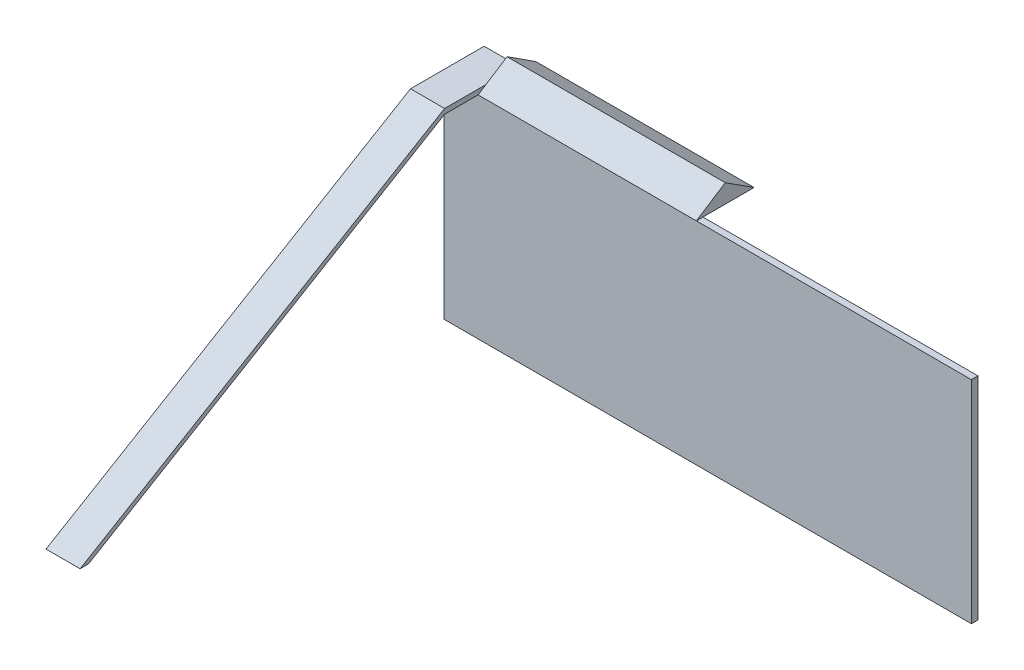
SolidWorks part; units mm, degrees
ref_plane "Front Plane" through (0, 0, 0) normal (0, 0, 1) x (1, 0, 0)
ref_plane "Top Plane" through (0, 0, 0) normal (0, 1, 0) x (1, 0, 0)
ref_plane "Right Plane" through (0, 0, 0) normal (1, 0, 0) x (0, 0, -1)
sketch "Sketch1" plane through (0, 0, 0) normal (0, 0, 1) x (1, 0, 0)
  line L1 (0, 0) -> (2170, 0)
  line L2 (0, 0) -> (0, 930)
  line L3 (0, 930) -> (2170, 930)
  line L4 (2170, 0) -> (2170, 930)
  line L5 (0, 930) -> (-150, 930)
  line L6 (0, 930) -> (0, 0)
  line L7 (0, 0) -> (-150, 0)
  line L8 (-150, 930) -> (-150, 0)
  line L9 (-150, 930) -> (0, 930)
  line L10 (-150, 930) -> (-150, 949)
  line L11 (-150, 949) -> (0, 949)
  line L12 (0, 930) -> (0, 949)
  line L13 (0, 930) -> (960, 930)
  line L14 (0, 930) -> (0, 1012)
  line L15 (0, 1012) -> (960, 1012)
  line L16 (960, 930) -> (960, 1012)
  dimension "D1" = 150
  dimension "D2" = 2170
  dimension "D3" = 930
  dimension "D4" = 19
  dimension "D5" = 960
  dimension "D6" = 82
extrude "Boss-Extrude1" add sketch "Sketch1" against normal blind 29 contours L1 L4 L3 L2 | L5 L8 L7 L2
sketch "Sketch2" plane through (-150, 0, 0) normal (-1, 0, 0) x (0, 0, 1)
  line L0 (147.5, 930) -> (1713.946, 0)
  line L1 (1713.946, 0) -> (1751.1638, 0)
  line L2 (1751.1638, 0) -> (147.5, 952.0963)
  line L3 (147.5, 952.0963) -> (147.5, 930)
  line L5 (-29, 0) -> (0, 0) construction
  line L6 (147.5, 930) -> (-176.5, 930)
  line L7 (147.5, 930) -> (147.5, 952.0963)
  line L8 (147.5, 952.0963) -> (-176.5, 952.0963)
  line L9 (-176.5, 930) -> (-176.5, 952.0963)
  point P10 (-14.5, 0)
  point P11 (-14.5, 930)
  line M6 (0, 930) -> (-29, 930)
  dimension "D1" = 19
  dimension "D2" = 1865
  dimension "D3" = 324
extrude "Boss-Extrude2" add sketch "Sketch2" against normal blind 150 contours L9 L6 L3 L8 M6 | L2 L3 L0 L1
sketch "Sketch3" plane through (0, 0, 0) normal (1, 0, 0) x (0, 0, -1)
  line L0 (0, 930) -> (254, 930)
  line L1 (29, 930) -> (176.5, 930) construction
  line L2 (254, 930) -> (127, 1012)
  line L3 (127, 1012) -> (0, 930)
  point P5 (0, 0)
  point P7 (0, 0)
  point P8 (0, 0)
  point P9 (127, 930)
  dimension "D1" = 254
  dimension "D3" = 82
extrude "Boss-Extrude3" add sketch "Sketch3" along normal blind 960
